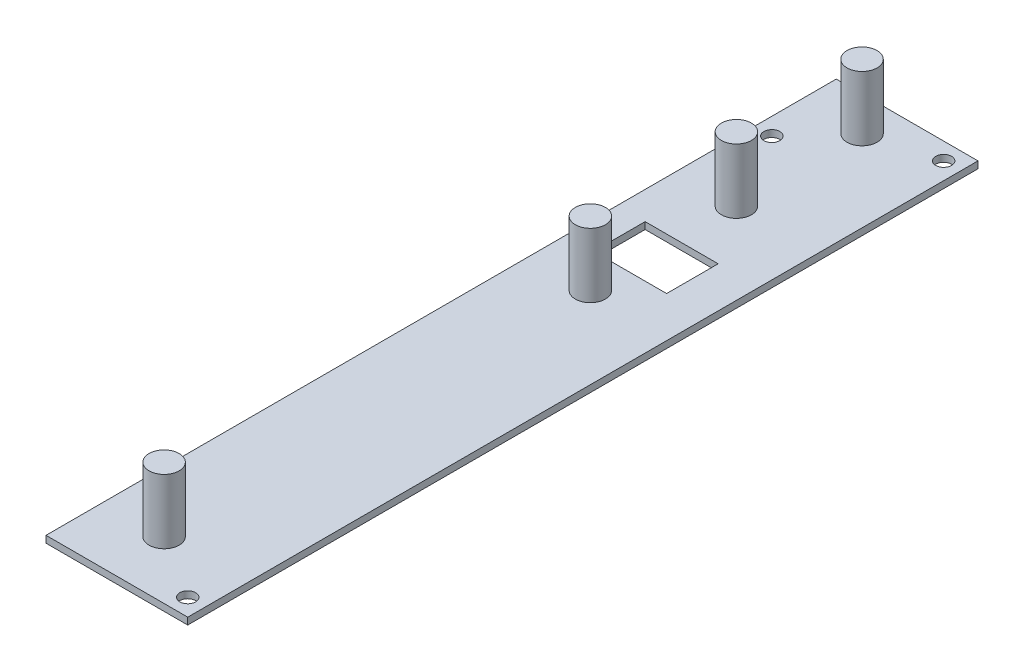
SolidWorks part; units mm, degrees
ref_plane "Front Plane" through (0, 0, 0) normal (0, 0, 1) x (1, 0, 0)
ref_plane "Top Plane" through (0, 0, 0) normal (0, 1, 0) x (1, 0, 0)
ref_plane "Right Plane" through (0, 0, 0) normal (1, 0, 0) x (0, 0, -1)
sketch "Sketch1" plane through (0, 0, 0) normal (0, 1, 0) x (1, 0, 0)
  line L1 (-16.5, 92) -> (16.5, 92)
  line L2 (-16.5, 92) -> (-16.5, -92)
  line L3 (-16.5, -92) -> (16.5, -92)
  line L4 (16.5, 92) -> (16.5, -92)
  line L5 (-16.5, 92) -> (16.5, -92) construction
  line L6 (-16.5, -92) -> (16.5, 92) construction
  point P0 (0, 0)
  dimension "D1" = 33
  dimension "D2" = 184
extrude "Boss-Extrude1" add sketch "Sketch1" along normal blind 1.6
sketch "Sketch2" plane through (0, 1.6, 0) normal (0, 1, 0) x (1, 0, 0)
  line L0 (16.5, 92) -> (-16.5, 92) construction
  line L1 (-16.5, 92) -> (-16.5, -92) construction
  line L2 (16.5, -92) -> (16.5, 92) construction
  line L3 (-16.5, -92) -> (16.5, -92) construction
  circle A2 centre (-12.5, 73) radius 1.85
  circle A3 centre (12.5, 88) radius 1.85
  circle A4 centre (12.5, -88) radius 1.85
  point P0 (0, 0)
  dimension "D2" = 3.7
  dimension "D3" = 19
  dimension "D4" = 4
  dimension "D5" = 4
  dimension "D6" = 4
  dimension "D7" = 4
extrude "Cut-Extrude1" cut sketch "Sketch2" against normal through all
sketch "Sketch3" plane through (0, 1.6, 0) normal (0, 1, 0) x (1, 0, 0)
  line L0 (16.5, 92) -> (-16.5, 92) construction
  line L1 (-16.5, 92) -> (-16.5, -92) construction
  circle A0 centre (-2.5, 84) radius 3.5
  circle A1 centre (-2.5, 54.75) radius 3.5
  circle A2 centre (-2.5, 20.75) radius 3.5
  circle A3 centre (-2.5, -78.5) radius 3.5
  dimension "D3" = 7
  dimension "D1" = 8
  dimension "D2" = 14
  dimension "D4" = 37.25
  dimension "D5" = 71.25
  dimension "D6" = 170.5
extrude "Boss-Extrude2" add sketch "Sketch3" along normal blind 15
sketch "Sketch4" plane through (0, 1.6, 0) normal (0, 1, 0) x (1, 0, 0)
  line L0 (-16.5, 92) -> (-16.5, -92) construction
  line L1 (-10, 41) -> (7, 41)
  line L2 (-10, 41) -> (-10, 29)
  line L3 (-10, 29) -> (7, 29)
  line L4 (7, 41) -> (7, 29)
  line L5 (16.5, 92) -> (-16.5, 92) construction
  dimension "D1" = 6.5
  dimension "D2" = 51
  dimension "D3" = 23.5
  dimension "D4" = 63
extrude "Cut-Extrude2" cut sketch "Sketch4" against normal through all
